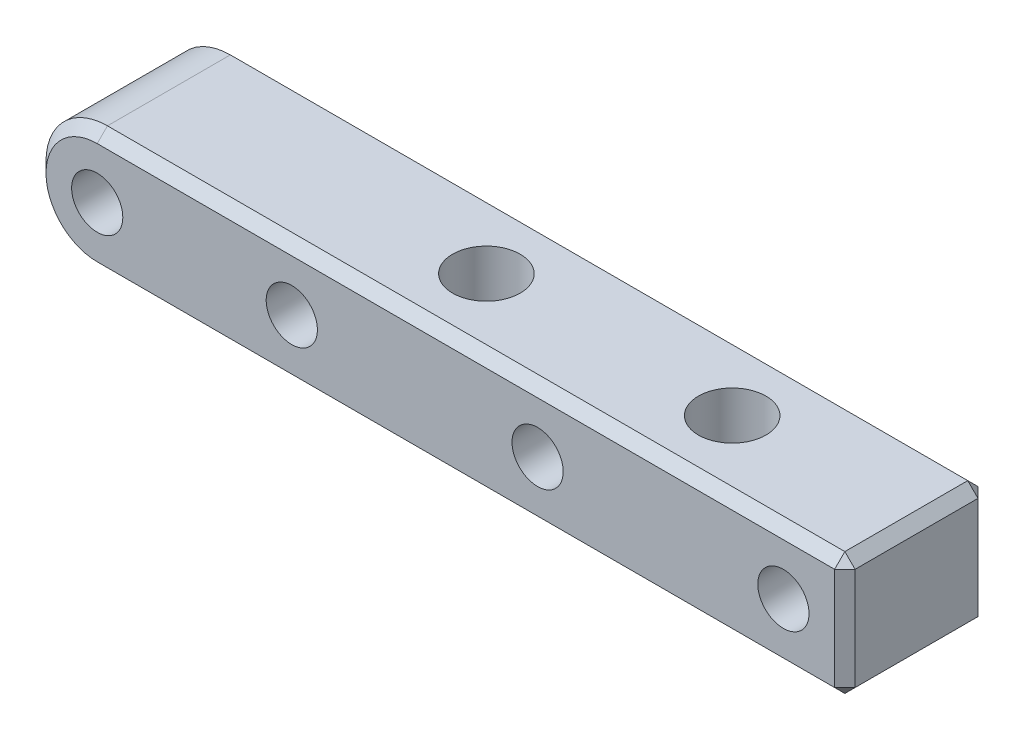
SolidWorks part; units mm, degrees
material "6061 合金"
ref_plane "前视基准面" through (0, 0, 0) normal (0, 0, 1) x (1, 0, 0)
ref_plane "上视基准面" through (0, 0, 0) normal (0, 1, 0) x (1, 0, 0)
ref_plane "右视基准面" through (0, 0, 0) normal (1, 0, 0) x (0, 0, -1)
sketch "草图2" plane through (0, 0, 0) normal (0, 0, 1) x (1, 0, 0)
  line L10 (3, 3) -> (3, -3)
  line L11 (0, 0) -> (-24, 0) construction
  line L41 (3, -3) -> (-33.5, -3)
  line L43 (-24, 0) -> (-33.5, 0) construction
  line L48 (-33.5, 3) -> (3, 3)
  circle A1 centre (-33.5, 0) radius 0.5
  circle A2 centre (-24, 0) radius 0.5
  circle A3 centre (-12, 0) radius 0.5
  circle A5 centre (0, 0) radius 0.5
  arc A9 (-33.5, 3) -> (-33.5, -3) centre (-33.5, 0) ccw
  dimension "D2" = 1
  dimension "D3" = 3
  dimension "D4" = 9.5
  dimension "D5" = 24
  dimension "D7" = 3
  dimension "D6" = 3
extrude "凸台-拉伸1" add sketch "草图2" along normal mid plane 7
hole_wizard "M3 螺纹孔1" positions "草图5" profile "草图4" tap size "M3" standard "GB" end condition through all
sketch "草图5" plane through (0, 0, 3.5) normal (0, 0, 1) x (1, 0, 0)
  point P0 (0, 0)
  point P3 (-12, 0)
  point P6 (-24, 0)
  point P9 (-33.5, 0)
sketch "草图4" plane through (0, 0, 3.5) normal (1, 0, 0) x (0, -1, 0)
  line L0 (0, 0) -> (0, 7)
  line L1 (0, 7) -> (1.25, 7)
  line L2 (1.25, 7) -> (1.25, 0)
  line L5 (1.25, 0) -> (0, 0)
  line L11 (0, -6.35) -> (0, 107.95) construction
  dimension "通孔螺纹孔钻头直径" = 2.5
  dimension "通孔螺纹孔钻头深度" = 7
cosmetic thread "孔螺蚊线1" parameters "D2"=3
cosmetic thread "孔螺蚊线2" parameters "D2"=3
cosmetic thread "孔螺蚊线3" parameters "D2"=3
cosmetic thread "孔螺蚊线4" parameters "D2"=3
hole_wizard "M4 螺纹孔1" positions "草图6" profile "草图7" tap size "M4" standard "GB" end condition through all
sketch "草图6" plane through (0, 3, 0) normal (0, 1, 0) x (1, 0, 0)
  line L0 (3, -3.5) -> (3, 3.5) construction
  line L1 (-18, 0) -> (0, 0) construction
  point P0 (-6, 0)
  point P2 (-18, 0)
  dimension "D1" = 9
  dimension "D2" = 12
sketch "草图7" plane through (-6, 3, 0) normal (1, 0, 0) x (0, 0, 1)
  line L0 (0, 0) -> (0, 6)
  line L1 (0, 6) -> (1.65, 6)
  line L2 (1.65, 6) -> (1.65, 0)
  line L5 (1.65, 0) -> (0, 0)
  line L11 (0, -6.35) -> (0, 107.95) construction
  dimension "通孔螺纹孔钻头直径" = 3.3
  dimension "通孔螺纹孔钻头深度" = 6
cosmetic thread "孔螺蚊线5" parameters "D2"=4
cosmetic thread "孔螺蚊线6" parameters "D2"=4
chamfer "倒角1" distance 0.5 angle 45 10 edges at (-15.25, -3, -3.5) (-15.25, -3, 3.5) (-36.5, 0, -3.5) (-36.5, 0, 3.5) (3, -3, 0) (3, 0, 3.5) (3, 0, -3.5) (-15.25, 3, -3.5) (3, 3, 0) (-15.25, 3, 3.5)
